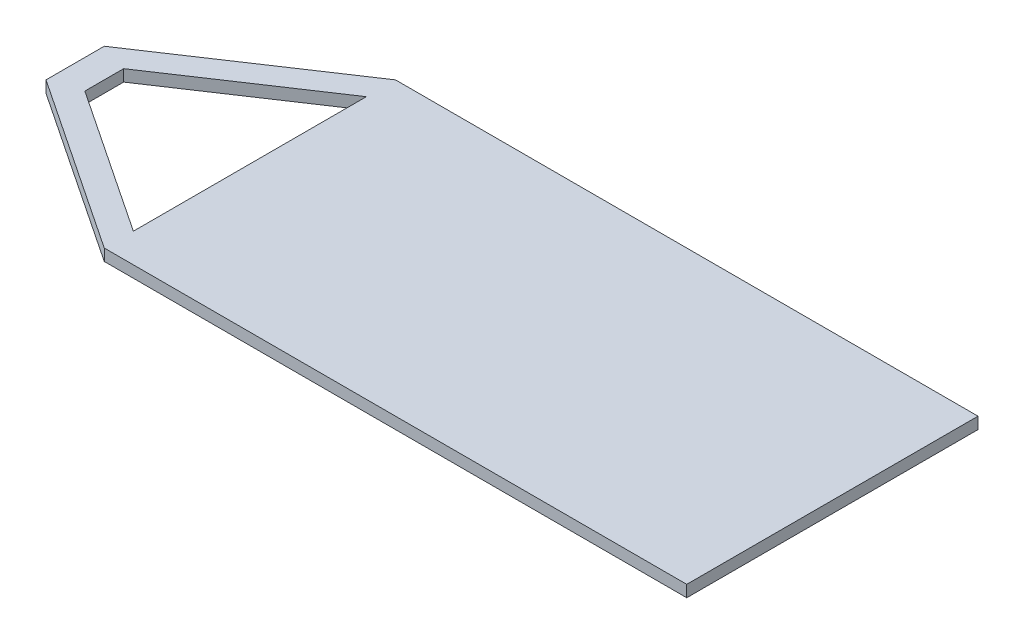
SolidWorks part; units mm, degrees
ref_plane "Front Plane" through (0, 0, 0) normal (0, 0, 1) x (1, 0, 0)
ref_plane "Top Plane" through (0, 0, 0) normal (0, 1, 0) x (1, 0, 0)
ref_plane "Right Plane" through (0, 0, 0) normal (1, 0, 0) x (0, 0, -1)
sketch "Sketch1" plane through (0, 0, 0) normal (0, 1, 0) x (1, 0, 0)
  line L0 (0, 5) -> (30, 25)
  line L1 (30, -25) -> (130, -25)
  line L2 (30, -20) -> (30, 20)
  line L3 (30, 25) -> (130, 25)
  line L4 (130, -25) -> (130, 25)
  line L5 (0, -5) -> (30, -25)
  line L6 (5, 3.3333) -> (30, 20)
  line L7 (5, -3.3333) -> (30, -20)
  line L8 (0, 5) -> (0, -5)
  line L9 (5, 3.3333) -> (5, -3.3333)
  line L10 (30, 25) -> (30, 20) construction
  line L11 (30, -20) -> (30, -25) construction
  point P4 (0, 0)
  dimension "D1" = 10
  dimension "D2" = 5
  dimension "D3" = 50
  dimension "D4" = 5
  dimension "D5" = 30
  dimension "D6" = 100
extrude "Boss-Extrude1" add sketch "Sketch1" along normal blind 2
